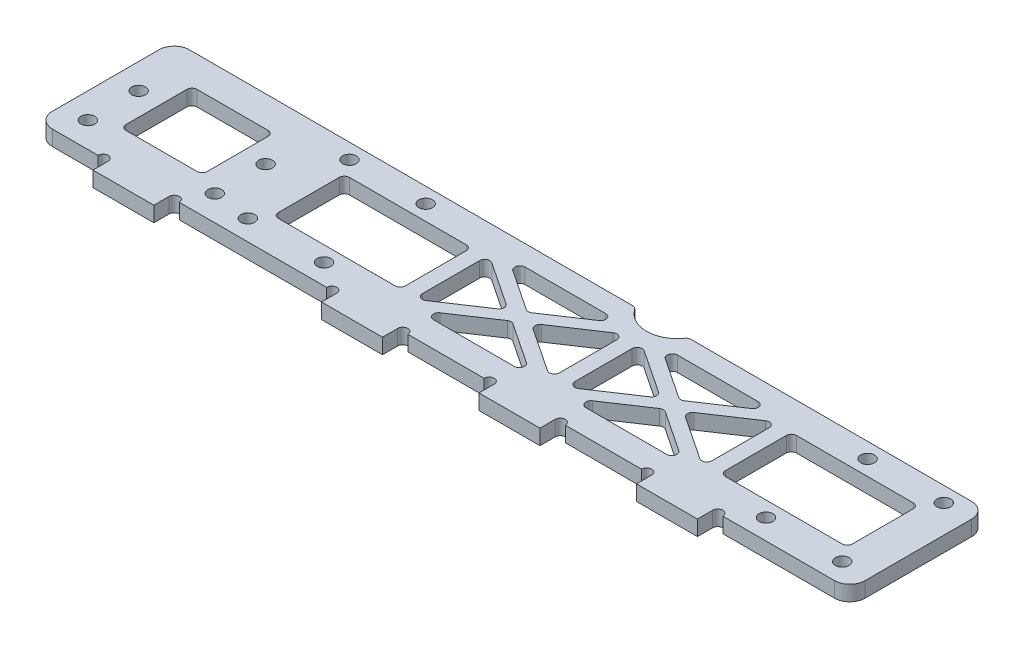
SolidWorks part; units mm, degrees
material "碳纤维"
ref_plane "前视基准面" through (0, 0, 0) normal (0, 0, 1) x (1, 0, 0)
ref_plane "上视基准面" through (0, 0, 0) normal (0, 1, 0) x (1, 0, 0)
ref_plane "右视基准面" through (0, 0, 0) normal (1, 0, 0) x (0, 0, -1)
sketch "草图1" plane through (0, 0, 0) normal (0, 1, 0) x (1, 0, 0)
  line L1 (-80, -13.5) -> (80, -13.5)
  line L2 (-80, -13.5) -> (-80, 13.5)
  line L3 (-80, 13.5) -> (80, 13.5)
  line L4 (80, -13.5) -> (80, 13.5)
  line L5 (0, 13.5) -> (0, -13.5) construction
  line L6 (-80, 0) -> (80, 0) construction
  point P0 (0, 0)
  dimension "D1" = 27
  dimension "D2" = 160
extrude "凸台-拉伸1" add sketch "草图1" along normal blind 3
sketch "草图2" plane through (0, 3, 0) normal (0, 1, 0) x (1, 0, 0)
  line L0 (80, 0.5) -> (-80, 0.5) construction
  line L1 (80, -13.5) -> (80, 13.5) construction
  line L2 (-80, 13.5) -> (-80, -13.5) construction
  line L3 (-80, -13.5) -> (80, -13.5) construction
  line L4 (16, 13.5) -> (16, -13.5) construction
  line L5 (47.5, -6.5) -> (72.5, -6.5)
  line L6 (47.5, -6.5) -> (47.5, 7.5)
  line L7 (47.5, 7.5) -> (72.5, 7.5)
  line L8 (72.5, -6.5) -> (72.5, 7.5)
  line L9 (60, 7.5) -> (60, -6.5) construction
  line L10 (47.5, 0.5) -> (72.5, 0.5) construction
  line L11 (80, 13.5) -> (-80, 13.5) construction
  line L12 (-15.5, 7.5) -> (-40.5, 7.5)
  line L13 (-40.5, -6.5) -> (-40.5, 7.5)
  line L14 (-15.5, -6.5) -> (-40.5, -6.5)
  line L15 (-15.5, -6.5) -> (-15.5, 7.5)
  line L16 (67, 13.5) -> (67, -13.5) construction
  circle A0 centre (74.5, 10.5) radius 1.35
  circle A1 centre (74.5, -9.5) radius 1.35
  circle A2 centre (59.5, -9.5) radius 1.35
  circle A3 centre (59.5, 10.5) radius 1.35
  circle A4 centre (-27.5, -9.5) radius 1.35
  circle A5 centre (-42.5, -9.5) radius 1.35
  circle A6 centre (-42.5, 10.5) radius 1.35
  circle A7 centre (-27.5, 10.5) radius 1.35
  point P8 (60, 0.5)
  dimension "D3" = 2.7
  dimension "D1" = 14
  dimension "D4" = 25
  dimension "D5" = 14
  dimension "D6" = 88
  dimension "D2" = 64
  dimension "D7" = 15
  dimension "D8" = 20
  dimension "D9" = 5.5
extrude "切除-拉伸2" cut sketch "草图2" against normal through all
ref_plane "基准面1" through (0, 0, -0.5) normal (0, 0, 1) x (1, 0, 0)
fillet "圆角1" radius 1 8 edges at (72.5, 1.5, 6.5) (47.5, 1.5, 6.5) (47.5, 1.5, -7.5) (72.5, 1.5, -7.5) (-15.5, 1.5, 6.5) (-40.5, 1.5, 6.5) (-40.5, 1.5, -7.5) (-15.5, 1.5, -7.5)
sketch "草图3" plane through (0, 0, 0) normal (0, -1, 0) x (1, 0, 0)
  line L0 (-80, 13.5) -> (80, 13.5) construction
  line L1 (53, 13.5) -> (41, 13.5)
  line L2 (53, 13.5) -> (53, 16.5)
  line L3 (53, 16.5) -> (41, 16.5)
  line L4 (41, 13.5) -> (41, 16.5)
  line L5 (47, 16.5) -> (47, 13.5) construction
  line L6 (53, 15) -> (41, 15) construction
  line L7 (-15.5, -0.5) -> (47.5, -0.5) construction
  line L9 (-15.5, 5.5) -> (-15.5, -6.5) construction
  line L22 (5.9294, -0.5) -> (-5.9294, -0.5) construction
  line L23 (16, -0.5) -> (16, 13.5) construction
  line L24 (-21, 16.5) -> (-9, 16.5)
  line L25 (-9, 13.5) -> (-9, 16.5)
  line L26 (-21, 13.5) -> (-9, 13.5)
  line L27 (-21, 13.5) -> (-21, 16.5)
  line L28 (47.5, -6.5) -> (47.5, 5.5) construction
  line L29 (-80, -13.5) -> (-80, 13.5) construction
  line L30 (22, 13.5) -> (10, 13.5)
  line L31 (22, 13.5) -> (22, 16.5)
  line L32 (22, 16.5) -> (10, 16.5)
  line L33 (10, 13.5) -> (10, 16.5)
  line L34 (16, 16.5) -> (16, 13.5) construction
  line L35 (22, 15) -> (10, 15) construction
  line L36 (-54, 13.5) -> (-66, 13.5)
  line L37 (-54, 13.5) -> (-54, 16.5)
  line L38 (-54, 16.5) -> (-66, 16.5)
  line L39 (-66, 13.5) -> (-66, 16.5)
  line L40 (-60, 16.5) -> (-60, 13.5) construction
  line L41 (-54, 15) -> (-66, 15) construction
  point P104 (-60, 15)
  point P140 (16, 15)
  point P188 (47, 15)
  dimension "D1" = 50
  dimension "D2" = 12
  dimension "D3" = 3
  dimension "D4" = 20
extrude "凸台-拉伸2" add sketch "草图3" against normal up to surface (3 mm away) up to face at (-42.5, 3, -11.85)
sketch "草图4" plane through (0, 0, 0) normal (0, -1, 0) x (1, 0, 0)
  line L0 (53, 13.5) -> (80, 13.5) construction
  line L1 (47, 16.5) -> (47, -13.5) construction
  line L2 (53, 16.5) -> (41, 16.5) construction
  line L3 (31.5, 13.5) -> (31.5, -13.5) construction
  line L4 (22, 13.5) -> (41, 13.5) construction
  line L5 (80, -13.5) -> (-80, -13.5) construction
  line L6 (16, 16.5) -> (16, -13.5) construction
  line L7 (22, 16.5) -> (10, 16.5) construction
  line L8 (-37.5, 13.5) -> (-37.5, -13.5) construction
  line L9 (-54, 13.5) -> (-21, 13.5) construction
  line L10 (53, 13.5) -> (53, 16.5) construction
  circle A0 centre (54, 13.5) radius 1
  circle A1 centre (40, 13.5) radius 1
  circle A2 centre (23, 13.5) radius 1
  circle A3 centre (9, 13.5) radius 1
  circle A4 centre (-8, 13.5) radius 1
  circle A5 centre (-22, 13.5) radius 1
  circle A6 centre (-53, 13.5) radius 1
  circle A7 centre (-67, 13.5) radius 1
  dimension "D1" = 2
extrude "切除-拉伸4" cut sketch "草图4" against normal through all
fillet "圆角2" radius 3 4 edges at (-80, 1.5, 13.5) (-80, 1.5, -13.5) (80, 1.5, 13.5) (80, 1.5, -13.5)
sketch "草图6" plane through (0, 0, 0) normal (0, -1, 0) x (1, 0, 0)
  line L0 (-80, -10.5) -> (-80, 10.5) construction
  line L1 (-50, 8.5) -> (-75, 8.5) construction
  line L2 (-50, 8.5) -> (-50, -1.5) construction
  line L3 (-50, -1.5) -> (-75, -1.5) construction
  line L4 (-75, 8.5) -> (-75, -1.5) construction
  line L5 (-62.5, -1.5) -> (-62.5, 8.5) construction
  line L6 (-50, 3.5) -> (-75, 3.5) construction
  line L7 (-52, 13.5) -> (-23, 13.5) construction
  circle A0 centre (-75, -1.5) radius 1.35
  circle A1 centre (-75, 8.5) radius 1.35
  circle A2 centre (-50, -1.5) radius 1.35
  circle A3 centre (-50, 8.5) radius 1.35
  point P0 (-62.5, 3.5)
  dimension "D2" = 2.7
  dimension "D1" = 25
  dimension "D3" = 5
  dimension "D4" = 10
  dimension "D5" = 10
extrude "切除-拉伸6" cut sketch "草图6" against normal through all
sketch "草图5" plane through (0, 0, 0) normal (0, -1, 0) x (1, 0, 0)
  line L0 (47.5, -0.5) -> (44.5, -0.5) construction
  line L5 (16, 16.5) -> (16, -13.5) construction
  line L6 (44.5, -9.5) -> (17.5, -9.5) construction
  line L7 (42.2465, -9.5) -> (31, -2.0023)
  line L8 (31, -2.0023) -> (19.7535, -9.5)
  line L9 (19.7535, -9.5) -> (42.2465, -9.5)
  line L10 (44.5, -9.5) -> (44.5, 8.5) construction
  line L11 (44.5, 8.5) -> (17.5, 8.5) construction
  line L12 (17.5, -9.5) -> (17.5, 8.5) construction
  line L13 (31, 8.5) -> (31, -9.5) construction
  line L14 (44.5, -0.5) -> (17.5, -0.5) construction
  line L21 (22, 16.5) -> (10, 16.5) construction
  line L22 (77, -13.5) -> (-77, -13.5) construction
  line L25 (47.5, -6.5) -> (47.5, 5.5) construction
  line L26 (44.5, -7.9977) -> (44.5, 6.9977)
  line L27 (44.5, 6.9977) -> (33.2535, -0.5)
  line L28 (33.2535, -0.5) -> (44.5, -7.9977)
  line L29 (44.5, -9.5) -> (31, -0.5) construction
  line L30 (31, 1.0023) -> (19.7535, 8.5)
  line L31 (42.2465, 8.5) -> (31, 1.0023)
  line L32 (19.7535, 8.5) -> (42.2465, 8.5)
  line L33 (17.5, 6.9977) -> (28.7465, -0.5)
  line L34 (17.5, -7.9977) -> (17.5, 6.9977)
  line L35 (28.7465, -0.5) -> (17.5, -7.9977)
  line L36 (14.5, -7.9977) -> (14.5, 6.9977)
  line L37 (3.2535, -0.5) -> (14.5, -7.9977)
  line L38 (14.5, 6.9977) -> (3.2535, -0.5)
  line L39 (-12.5, 6.9977) -> (-1.2535, -0.5)
  line L40 (-12.5, -7.9977) -> (-12.5, 6.9977)
  line L41 (-1.2535, -0.5) -> (-12.5, -7.9977)
  line L42 (-10.2465, 8.5) -> (1, 1.0023)
  line L43 (12.2465, 8.5) -> (-10.2465, 8.5)
  line L44 (1, 1.0023) -> (12.2465, 8.5)
  line L45 (1, -2.0023) -> (12.2465, -9.5)
  line L46 (-10.2465, -9.5) -> (1, -2.0023)
  line L47 (12.2465, -9.5) -> (-10.2465, -9.5)
  line L48 (-75, 8.5) -> (-50, 8.5) construction
  line L49 (-54.5, -7.5) -> (-70.5, -7.5)
  line L50 (-54.5, -7.5) -> (-54.5, 6.5)
  line L51 (-54.5, 6.5) -> (-70.5, 6.5)
  line L52 (-70.5, -7.5) -> (-70.5, 6.5)
  line L53 (-62.5, 6.5) -> (-62.5, -7.5) construction
  line L54 (-54.5, -0.5) -> (-70.5, -0.5) construction
  line L55 (-62.5, 8.5) -> (-62.5, 6.5) construction
  line L56 (-16.5, -7.5) -> (-39.5, -7.5) construction
  line L57 (-39.5, 6.5) -> (-16.5, 6.5) construction
  point P128 (31, -0.5)
  point P223 (-62.5, -0.5)
  dimension "D1" = 1.5
  dimension "D2" = 3
  dimension "D3" = 4
  dimension "D4" = 2.5
  dimension "D5" = 16
extrude "切除-拉伸5" cut sketch "草图5" against normal through all
sketch "草图7" plane through (0, 0, 0) normal (0, -1, 0) x (1, 0, 0)
  line L0 (59.5, -10.5) -> (-27.5, -10.5) construction
  line L1 (-7, 13.5) -> (8, 13.5) construction
  line L2 (16, -16.5) -> (16, -10.5) construction
  circle A0 centre (16, -16.5) radius 6
  dimension "D2" = 12
  dimension "D1" = 30
extrude "切除-拉伸7" cut sketch "草图7" against normal through all
fillet "圆角3" radius 1 30 edges at (31, 1.5, -2.0023) (42.2465, 1.5, -9.5) (19.7535, 1.5, -9.5) (1, 1.5, 1.0023) (-10.2465, 1.5, 8.5) (12.2465, 1.5, 8.5) (-1.2535, 1.5, -0.5) (-12.5, 1.5, -7.9977) (-12.5, 1.5, 6.9977) (12.2465, 1.5, -9.5) (-10.2465, 1.5, -9.5) (1, 1.5, -2.0023) (19.7535, 1.5, 8.5) (42.2465, 1.5, 8.5) (31, 1.5, 1.0023) (44.5, 1.5, 6.9977) (33.2535, 1.5, -0.5) (28.7465, 1.5, -0.5) (17.5, 1.5, -7.9977) (17.5, 1.5, 6.9977) (14.5, 1.5, 6.9977) (14.5, 1.5, -7.9977) (3.2535, 1.5, -0.5) (44.5, 1.5, -7.9977) (-70.5, 1.5, -7.5) (-54.5, 1.5, 6.5) (-54.5, 1.5, -7.5) (-70.5, 1.5, 6.5) (21.1962, 1.5, -13.5) (10.8038, 1.5, -13.5)
move or copy body "实体-移动/复制1" [suppressed] bodies to move or copy 112
